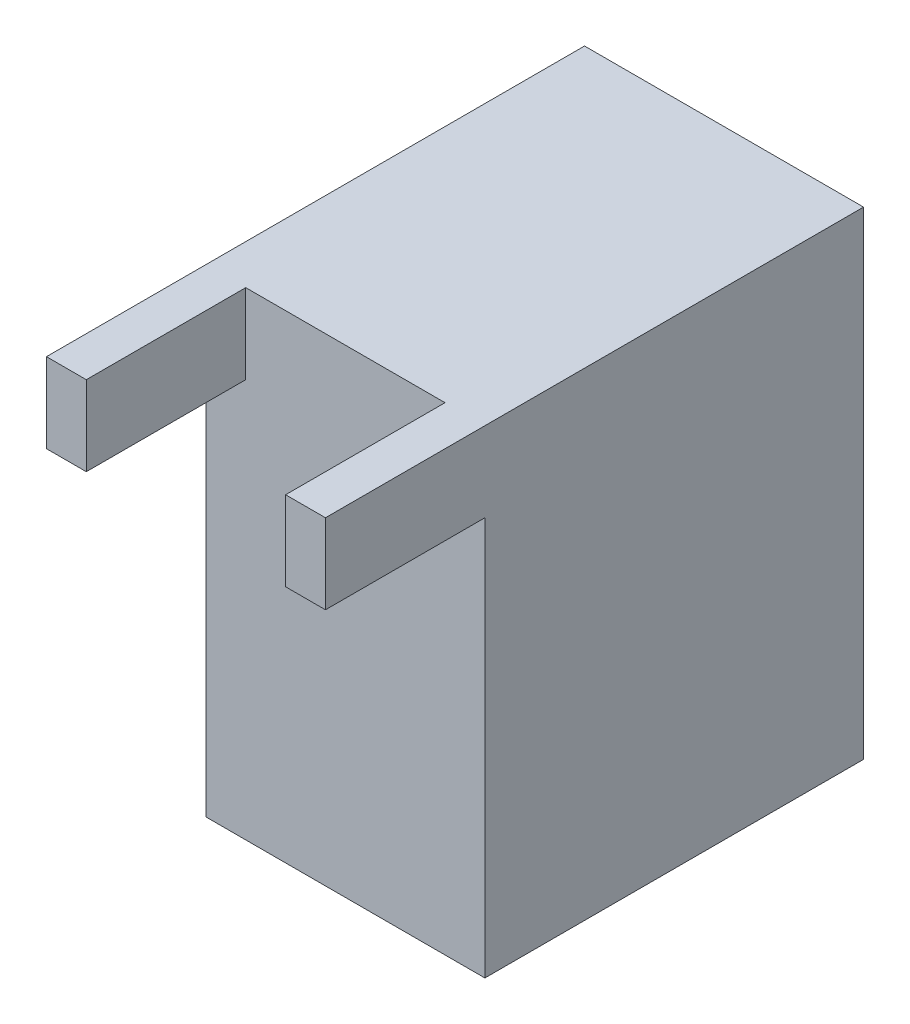
SolidWorks part; units mm, degrees
ref_plane "Front Plane" through (0, 0, 0) normal (0, 0, 1) x (1, 0, 0)
ref_plane "Top Plane" through (0, 0, 0) normal (0, 1, 0) x (1, 0, 0)
ref_plane "Right Plane" through (0, 0, 0) normal (1, 0, 0) x (0, 0, -1)
sketch "Sketch1" plane through (0, 0, 0) normal (0, 1, 0) x (1, 0, 0)
  line L1 (-1.8482, 5.6657) -> (5.1518, 5.6657)
  line L2 (-1.8482, 5.6657) -> (-1.8482, -3.8343)
  line L3 (-1.8482, -3.8343) -> (5.1518, -3.8343)
  line L4 (5.1518, 5.6657) -> (5.1518, -3.8343)
  dimension "D1" = 7
  dimension "D2" = 9.5
extrude "Boss-Extrude1" add sketch "Sketch1" along normal blind 12
sketch "Sketch3" plane through (0, 0, 0) normal (0, -1, 0) x (1, 0, 0)
  line L0 (5.1518, -5.6657) -> (-1.8482, -5.6657) construction
  line L1 (5.1518, 3.8343) -> (5.1518, -5.6657) construction
  circle A0 centre (1.6518, -0.1657) radius 3.15
  dimension "D1" = 5.5
  dimension "D2" = 3.5
  dimension "D3" = 6.3
extrude "Cut-Extrude2" cut sketch "Sketch3" against normal blind 11
sketch "Sketch4" plane through (0, 0, 3.8343) normal (0, 0, 1) x (1, 0, 0)
  line L9 (-1.8482, 12) -> (-0.8482, 12)
  line L10 (-1.8482, 12) -> (-1.8482, 10)
  line L11 (-1.8482, 10) -> (-0.8482, 10)
  line L12 (-0.8482, 12) -> (-0.8482, 10)
  line L13 (5.1518, 12) -> (4.1518, 12)
  line L14 (5.1518, 12) -> (5.1518, 10)
  line L15 (5.1518, 10) -> (4.1518, 10)
  line L16 (4.1518, 12) -> (4.1518, 10)
  dimension "D1" = 1
  dimension "D2" = 2
extrude "Boss-Extrude2" add sketch "Sketch4" along normal blind 4
